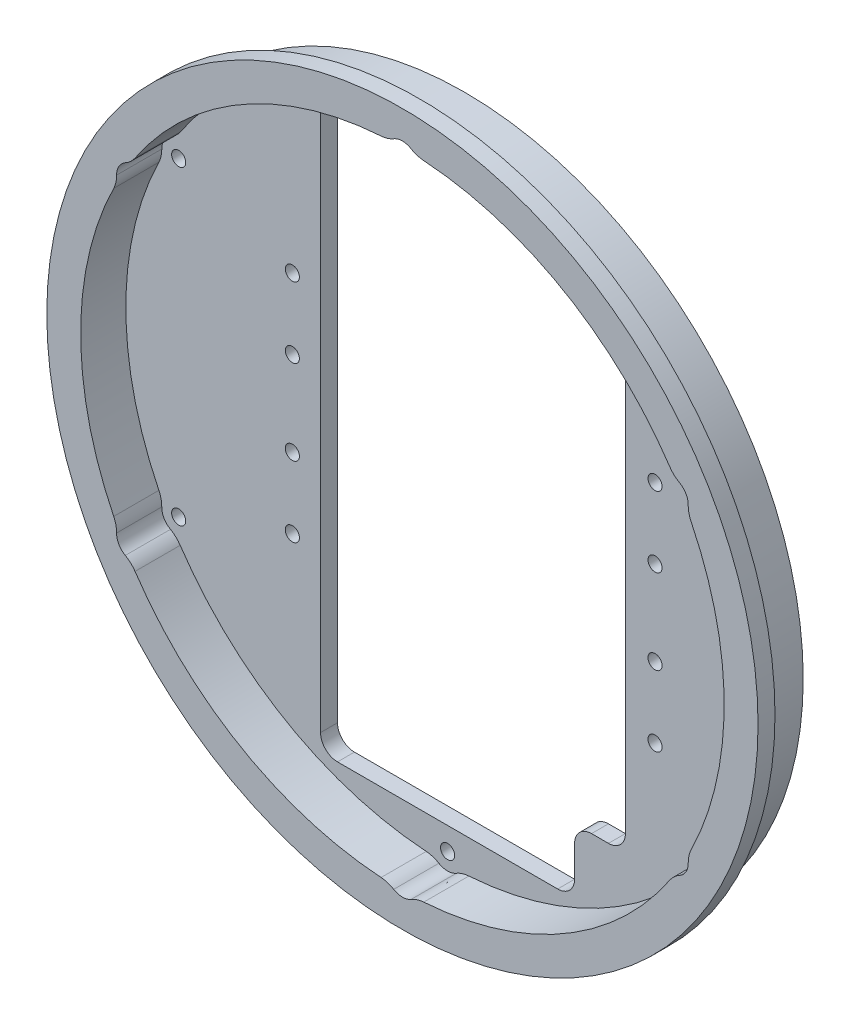
SolidWorks part; units mm, degrees
ref_plane "前视基准面" through (0, 0, 0) normal (0, 0, 1) x (1, 0, 0)
ref_plane "上视基准面" through (0, 0, 0) normal (0, 1, 0) x (1, 0, 0)
ref_plane "右视基准面" through (0, 0, 0) normal (1, 0, 0) x (0, 0, -1)
sketch "草图1" plane through (0, 0, 0) normal (0, 0, 1) x (1, 0, 0)
  circle A0 centre (0, 0) radius 60
  dimension "D1" = 120
extrude "凸台-拉伸1" add sketch "草图1" along normal blind 3
sketch "草图2" plane through (0, 0, 3) normal (0, 0, 1) x (1, 0, 0)
  circle A0 centre (0, 0) radius 60
  circle A1 centre (0, 0) radius 57
  circle A2 centre (0, 0) radius 60 construction
  dimension "D1" = 3
extrude "凸台-拉伸2" add sketch "草图2" along normal blind 8
sketch "草图3" plane through (0, 0, 11) normal (0, 0, 1) x (1, 0, 0)
  circle A0 centre (0, 0) radius 63
  circle A1 centre (0, 0) radius 60
  circle A2 centre (0, 0) radius 60 construction
  dimension "D1" = 3
extrude "凸台-拉伸3" add sketch "草图3" against normal blind 3
sketch "草图4" plane through (0, 0, 3) normal (0, 0, 1) x (1, 0, 0)
  line L1 (-22.5, -51) -> (22.5, -51)
  line L2 (-22.5, -51) -> (-22.5, 51)
  line L3 (-22.5, 51) -> (22.5, 51)
  line L4 (22.5, -51) -> (22.5, 51)
  line L5 (-22.5, -51) -> (22.5, 51) construction
  line L6 (-22.5, 51) -> (22.5, -51) construction
  point P0 (0, 0)
  dimension "D1" = 102
  dimension "D2" = 45
extrude "切除-拉伸1" cut sketch "草图4" against normal up to next
sketch "草图5" plane through (0, 0, 3) normal (0, 0, 1) x (1, 0, 0)
  line L0 (0, 0) -> (57, 0) construction
  line L1 (22.5, -51) -> (22.5, 51) construction
  line L2 (31.5, -39.5) -> (22.5, -39.5)
  line L3 (31.5, -39.5) -> (31.5, 39.5)
  line L4 (31.5, 39.5) -> (22.5, 39.5)
  line L5 (22.5, -39.5) -> (22.5, 39.5)
  line L6 (31.5, -39.5) -> (22.5, 39.5) construction
  line L7 (31.5, 39.5) -> (22.5, -39.5) construction
  circle A0 centre (0, 0) radius 57 construction
  point P6 (27, 0)
  dimension "D1" = 79
  dimension "D2" = 9
extrude "切除-拉伸2" cut sketch "草图5" against normal up to next
fillet "圆角3" radius 3 8 edges at (31.5, -39.5, 1.5) (22.5, -39.5, 1.5) (22.5, -51, 1.5) (-22.5, -51, 1.5) (-22.5, 51, 1.5) (22.5, 39.5, 1.5) (31.5, 39.5, 1.5) (22.5, 51, 1.5)
sketch "草图6" plane through (0, 0, 3) normal (0, 0, 1) x (1, 0, 0)
  line L0 (-57, 0) -> (57, 0) construction
  line L1 (-22.5, 48) -> (-22.5, -48) construction
  line L2 (-32.5, -25) -> (-22.5, -25) construction
  line L3 (-32.5, -25) -> (-32.5, 25) construction
  line L4 (-32.5, 25) -> (-22.5, 25) construction
  line L5 (-22.5, -25) -> (-22.5, 25) construction
  line L6 (-32.5, -25) -> (-22.5, 25) construction
  line L7 (-32.5, 25) -> (-22.5, -25) construction
  line L8 (31.5, -36.5) -> (31.5, 36.5) construction
  line L9 (42, -25) -> (31.5, -25) construction
  line L10 (42, -25) -> (42, 25) construction
  line L11 (42, 25) -> (31.5, 25) construction
  line L12 (31.5, -25) -> (31.5, 25) construction
  line L13 (42, -25) -> (31.5, 25) construction
  line L14 (42, 25) -> (31.5, -25) construction
  line L15 (-27.5, 25) -> (-27.5, -25) construction
  line L16 (36.75, 25) -> (36.75, -25) construction
  circle A0 centre (0, 0) radius 57 construction
  circle A1 centre (0, 0) radius 57 construction
  circle A2 centre (-27.5, 7.5) radius 1.25
  circle A3 centre (-27.5, 20) radius 1.25
  circle A4 centre (36.75, 7.5) radius 1.25
  circle A5 centre (36.75, 20) radius 1.25
  circle A6 centre (36.75, -7.5) radius 1.25
  circle A7 centre (-27.5, -7.5) radius 1.25
  circle A8 centre (-27.5, -20) radius 1.25
  circle A9 centre (36.75, -20) radius 1.25
  point P7 (-27.5, 0)
  point P14 (36.75, 0)
  dimension "D5" = 15
  dimension "D6" = 15
  dimension "D7" = 40
  dimension "D8" = 40
  dimension "D9" = 2.5
  dimension "D1" = 10.5
  dimension "D2" = 10
  dimension "D3" = 50
  dimension "D4" = 50
extrude "切除-拉伸3" cut sketch "草图6" against normal up to next
cosmetic thread "装饰螺纹线1" parameters "D2"=3
cosmetic thread "装饰螺纹线2" parameters "D2"=3
cosmetic thread "装饰螺纹线3" parameters "D2"=3
cosmetic thread "装饰螺纹线4" parameters "D2"=3
cosmetic thread "装饰螺纹线5" parameters "D2"=3
cosmetic thread "装饰螺纹线6" parameters "D2"=3
cosmetic thread "装饰螺纹线7" parameters "D2"=3
cosmetic thread "装饰螺纹线8" parameters "D2"=3
sketch "草图7" plane through (0, 0, 0) normal (0, 0, -1) x (-1, 0, 0)
  line L1 (0, 55) -> (-47.6314, 27.5) construction
  line L2 (-47.6314, 27.5) -> (-47.6314, -27.5) construction
  line L3 (-47.6314, -27.5) -> (0, -55) construction
  line L4 (0, -55) -> (47.6314, -27.5) construction
  line L5 (47.6314, -27.5) -> (47.6314, 27.5) construction
  line L6 (47.6314, 27.5) -> (0, 55) construction
  circle A0 centre (0, 0) radius 55 construction
  circle A1 centre (0, 0) radius 47.6314 construction
  circle A2 centre (0, 55) radius 1.25
  circle A3 centre (47.6314, 27.5) radius 1.25
  circle A4 centre (47.6314, -27.5) radius 1.25
  circle A5 centre (0, -55) radius 1.25
  circle A6 centre (-47.6314, -27.5) radius 1.25
  circle A7 centre (-47.6314, 27.5) radius 1.25
  point P24 (0, 0)
  dimension "D1" = 110
  dimension "D3" = 2.5
  dimension "D2" = 6
extrude "切除-拉伸4" cut sketch "草图7" against normal up to next
cosmetic thread "装饰螺纹线9" parameters "D2"=3
cosmetic thread "装饰螺纹线10" parameters "D2"=3
cosmetic thread "装饰螺纹线11" parameters "D2"=3
cosmetic thread "装饰螺纹线12" parameters "D2"=3
cosmetic thread "装饰螺纹线13" parameters "D2"=3
cosmetic thread "装饰螺纹线14" parameters "D2"=3
sketch "草图8" plane through (0, 0, 3) normal (0, 0, 1) x (1, 0, 0)
  circle A0 centre (-47.6314, 27.5) radius 3
  circle A1 centre (0, 55) radius 3
  circle A2 centre (47.6314, 27.5) radius 3
  circle A3 centre (47.6314, -27.5) radius 3
  circle A4 centre (0, -55) radius 3
  circle A5 centre (-47.6314, -27.5) radius 3
  point P16 (0, 0)
  dimension "D2" = 6
  dimension "D1" = 6
extrude "切除-拉伸5" cut sketch "草图8" along normal blind 8
fillet "圆角4" radius 5 12 edges at (2.2759, -56.9545, 7) (-2.2759, -56.9545, 7) (50.462, -26.5063, 7) (48.1861, -30.4483, 7) (48.1861, 30.4483, 7) (50.462, 26.5063, 7) (-2.2759, 56.9545, 7) (2.2759, 56.9545, 7) (-50.462, 26.5063, 7) (-48.1861, 30.4483, 7) (-48.1861, -30.4483, 7) (-50.462, -26.5063, 7)
